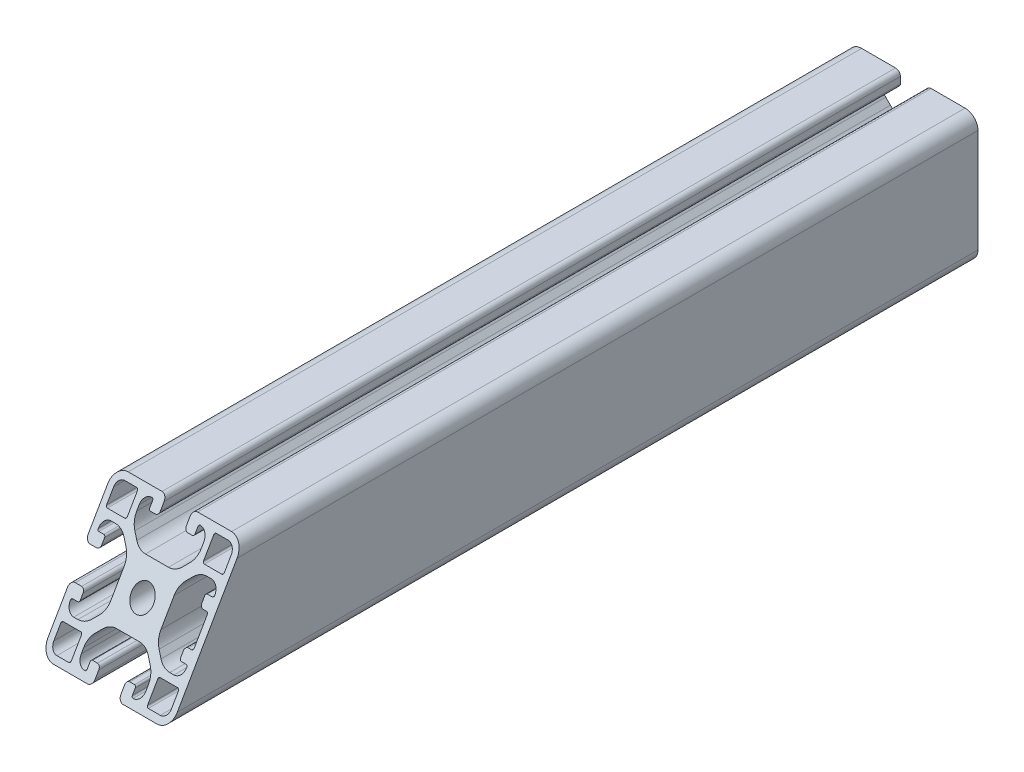
SolidWorks part; units mm, degrees
ref_plane "Piano frontale" through (0, 0, 0) normal (0, 0, 1) x (1, 0, 0)
ref_plane "Piano superiore" through (0, 0, 0) normal (0, 1, 0) x (1, 0, 0)
ref_plane "Piano destro" through (0, 0, 0) normal (1, 0, 0) x (0, 0, -1)
ref_plane "Piano1" through (0, 0, -340) normal (0, 0, -1) x (-1, 0, 0)
sketch "Schizzo1" plane through (0, 0, -340) normal (0, 0, -1) x (-1, 0, 0)
  line L0 (-12.3, -18.2) -> (-16, -18.2)
  line L1 (-18.2, -16) -> (-18.2, -12.3)
  line L2 (-17.7, -11.8) -> (-12.3, -11.8)
  line L3 (-11.8, -12.3) -> (-11.8, -17.7)
  line L4 (-11.8, 17.7) -> (-11.8, 12.3)
  line L5 (-12.3, 11.8) -> (-17.7, 11.8)
  line L6 (-18.2, 12.3) -> (-18.2, 16)
  line L7 (-16, 18.2) -> (-12.3, 18.2)
  line L8 (18.2, 16) -> (18.2, 12.3)
  line L9 (17.7, 11.8) -> (12.3, 11.8)
  line L10 (11.8, 12.3) -> (11.8, 17.7)
  line L11 (12.3, 18.2) -> (16, 18.2)
  line L12 (6.5, -15.5) -> (5, -15.5)
  line L13 (4, -16.5) -> (4, -18.5)
  line L14 (5.5, -20) -> (16, -20)
  line L15 (20, -16) -> (20, -5.5)
  line L16 (18.5, -4) -> (16.5, -4)
  line L17 (15.5, -5) -> (15.5, -6.5)
  line L18 (16, -7) -> (17.55, -7)
  line L19 (18, -7.45) -> (18, -7.5)
  line L20 (15.5, -10) -> (14.1924, -10)
  line L21 (10.6569, -8.5355) -> (9.2145, -7.0931)
  line L22 (7.75, -3.5576) -> (7.75, 3.5576)
  line L23 (9.2145, 7.0931) -> (10.6569, 8.5355)
  line L24 (14.1924, 10) -> (15.5, 10)
  line L25 (18, 7.5) -> (18, 7.45)
  line L26 (17.55, 7) -> (16, 7)
  line L27 (15.5, 6.5) -> (15.5, 5)
  line L28 (16.5, 4) -> (18.5, 4)
  line L29 (20, 5.5) -> (20, 16)
  line L30 (16, 20) -> (5.5, 20)
  line L31 (4, 18.5) -> (4, 16.5)
  line L32 (5, 15.5) -> (6.5, 15.5)
  line L33 (7, 16) -> (7, 17.55)
  line L34 (7.45, 18) -> (7.5, 18)
  line L35 (10, 15.5) -> (10, 14.1924)
  line L36 (8.5355, 10.6569) -> (7.0931, 9.2145)
  line L37 (3.5576, 7.75) -> (-3.5576, 7.75)
  line L38 (-7.0931, 9.2145) -> (-8.5355, 10.6569)
  line L39 (-10, 14.1924) -> (-10, 15.5)
  line L40 (-7.5, 18) -> (-7.45, 18)
  line L41 (-7, 17.55) -> (-7, 16)
  line L42 (-6.5, 15.5) -> (-5, 15.5)
  line L43 (-4, 16.5) -> (-4, 18.5)
  line L44 (-5.5, 20) -> (-16, 20)
  line L45 (-20, 16) -> (-20, -16)
  line L46 (-16, -20) -> (-5.5, -20)
  line L47 (-4, -18.5) -> (-4, -16.5)
  line L48 (-5, -15.5) -> (-6.5, -15.5)
  line L49 (-7, -16) -> (-7, -17.55)
  line L50 (-7.45, -18) -> (-7.5, -18)
  line L51 (-10, -15.5) -> (-10, -14.1924)
  line L52 (-8.5355, -10.6569) -> (-7.0931, -9.2145)
  line L53 (-3.5576, -7.75) -> (3.5576, -7.75)
  line L54 (7.0931, -9.2145) -> (8.5355, -10.6569)
  line L55 (10, -14.1924) -> (10, -15.5)
  line L56 (7.5, -18) -> (7.45, -18)
  line L57 (7, -17.55) -> (7, -16)
  line L58 (18.2, -12.3) -> (18.2, -16)
  line L59 (16, -18.2) -> (12.3, -18.2)
  line L60 (11.8, -17.7) -> (11.8, -12.3)
  line L61 (12.3, -11.8) -> (17.7, -11.8)
  line L62 (-16, 7) -> (-17.5, 7)
  line L63 (-15.5, 10) -> (-14.1924, 10)
  line L64 (-10.6569, 8.5355) -> (-9.2145, 7.0931)
  line L65 (-7.75, 3.5576) -> (-7.75, -3.5576)
  line L66 (-9.2145, -7.0931) -> (-10.6569, -8.5355)
  line L67 (-14.1924, -10) -> (-15.5, -10)
  line L68 (-17.5, -7) -> (-16, -7)
  line L69 (-15.5, -6.5) -> (-15.5, -5)
  line L70 (-16.5, -4) -> (-17.5, -4)
  line L71 (-18, -3.5) -> (-18, 3.5)
  line L72 (-17.5, 4) -> (-16.5, 4)
  line L73 (-15.5, 5) -> (-15.5, 6.5)
  arc A0 (-16, -18.2) -> (-18.2, -16) centre (-16, -16) cw
  arc A1 (-18.2, -12.3) -> (-17.7, -11.8) centre (-17.7, -12.3) cw
  arc A2 (-12.3, -11.8) -> (-11.8, -12.3) centre (-12.3, -12.3) cw
  arc A3 (-11.8, -17.7) -> (-12.3, -18.2) centre (-12.3, -17.7) cw
  arc A4 (-12.3, 18.2) -> (-11.8, 17.7) centre (-12.3, 17.7) cw
  arc A5 (-11.8, 12.3) -> (-12.3, 11.8) centre (-12.3, 12.3) cw
  arc A6 (-17.7, 11.8) -> (-18.2, 12.3) centre (-17.7, 12.3) cw
  arc A7 (-18.2, 16) -> (-16, 18.2) centre (-16, 16) cw
  arc A8 (16, 18.2) -> (18.2, 16) centre (16, 16) cw
  arc A9 (18.2, 12.3) -> (17.7, 11.8) centre (17.7, 12.3) cw
  arc A10 (12.3, 11.8) -> (11.8, 12.3) centre (12.3, 12.3) cw
  arc A11 (11.8, 17.7) -> (12.3, 18.2) centre (12.3, 17.7) cw
  arc A12 (5, -15.5) -> (4, -16.5) centre (5, -16.5) ccw
  arc A13 (4, -18.5) -> (5.5, -20) centre (5.5, -18.5) ccw
  arc A14 (16, -20) -> (20, -16) centre (16, -16) ccw
  arc A15 (20, -5.5) -> (18.5, -4) centre (18.5, -5.5) ccw
  arc A16 (16.5, -4) -> (15.5, -5) centre (16.5, -5) ccw
  arc A17 (15.5, -6.5) -> (16, -7) centre (16, -6.5) ccw
  arc A18 (17.55, -7) -> (18, -7.45) centre (17.55, -7.45) cw
  arc A19 (18, -7.5) -> (15.5, -10) centre (15.5, -7.5) cw
  arc A20 (14.1924, -10) -> (10.6569, -8.5355) centre (14.1924, -5) cw
  arc A21 (9.2145, -7.0931) -> (7.75, -3.5576) centre (12.75, -3.5576) cw
  arc A22 (7.75, 3.5576) -> (9.2145, 7.0931) centre (12.75, 3.5576) cw
  arc A23 (10.6569, 8.5355) -> (14.1924, 10) centre (14.1924, 5) cw
  arc A24 (15.5, 10) -> (18, 7.5) centre (15.5, 7.5) cw
  arc A25 (18, 7.45) -> (17.55, 7) centre (17.55, 7.45) cw
  arc A26 (16, 7) -> (15.5, 6.5) centre (16, 6.5) ccw
  arc A27 (15.5, 5) -> (16.5, 4) centre (16.5, 5) ccw
  arc A28 (18.5, 4) -> (20, 5.5) centre (18.5, 5.5) ccw
  arc A29 (20, 16) -> (16, 20) centre (16, 16) ccw
  arc A30 (5.5, 20) -> (4, 18.5) centre (5.5, 18.5) ccw
  arc A31 (4, 16.5) -> (5, 15.5) centre (5, 16.5) ccw
  arc A32 (6.5, 15.5) -> (7, 16) centre (6.5, 16) ccw
  arc A33 (7, 17.55) -> (7.45, 18) centre (7.45, 17.55) cw
  arc A34 (7.5, 18) -> (10, 15.5) centre (7.5, 15.5) cw
  arc A35 (10, 14.1924) -> (8.5355, 10.6569) centre (5, 14.1924) cw
  arc A36 (7.0931, 9.2145) -> (3.5576, 7.75) centre (3.5576, 12.75) cw
  arc A37 (-3.5576, 7.75) -> (-7.0931, 9.2145) centre (-3.5576, 12.75) cw
  arc A38 (-8.5355, 10.6569) -> (-10, 14.1924) centre (-5, 14.1924) cw
  arc A39 (-10, 15.5) -> (-7.5, 18) centre (-7.5, 15.5) cw
  arc A40 (-7.45, 18) -> (-7, 17.55) centre (-7.45, 17.55) cw
  arc A41 (-7, 16) -> (-6.5, 15.5) centre (-6.5, 16) ccw
  arc A42 (-5, 15.5) -> (-4, 16.5) centre (-5, 16.5) ccw
  arc A43 (-4, 18.5) -> (-5.5, 20) centre (-5.5, 18.5) ccw
  arc A44 (-16, 20) -> (-20, 16) centre (-16, 16) ccw
  arc A45 (-20, -16) -> (-16, -20) centre (-16, -16) ccw
  arc A46 (-5.5, -20) -> (-4, -18.5) centre (-5.5, -18.5) ccw
  arc A47 (-4, -16.5) -> (-5, -15.5) centre (-5, -16.5) ccw
  arc A48 (-6.5, -15.5) -> (-7, -16) centre (-6.5, -16) ccw
  arc A49 (-7, -17.55) -> (-7.45, -18) centre (-7.45, -17.55) cw
  arc A50 (-7.5, -18) -> (-10, -15.5) centre (-7.5, -15.5) cw
  arc A51 (-10, -14.1924) -> (-8.5355, -10.6569) centre (-5, -14.1924) cw
  arc A52 (-7.0931, -9.2145) -> (-3.5576, -7.75) centre (-3.5576, -12.75) cw
  arc A53 (3.5576, -7.75) -> (7.0931, -9.2145) centre (3.5576, -12.75) cw
  arc A54 (8.5355, -10.6569) -> (10, -14.1924) centre (5, -14.1924) cw
  arc A55 (10, -15.5) -> (7.5, -18) centre (7.5, -15.5) cw
  arc A56 (7.45, -18) -> (7, -17.55) centre (7.45, -17.55) cw
  arc A57 (7, -16) -> (6.5, -15.5) centre (6.5, -16) ccw
  arc A58 (17.7, -11.8) -> (18.2, -12.3) centre (17.7, -12.3) cw
  arc A59 (18.2, -16) -> (16, -18.2) centre (16, -16) cw
  arc A60 (12.3, -18.2) -> (11.8, -17.7) centre (12.3, -17.7) cw
  arc A61 (11.8, -12.3) -> (12.3, -11.8) centre (12.3, -12.3) cw
  circle A62 centre (0, 0) radius 3.4
  arc A63 (-15.5, 6.5) -> (-16, 7) centre (-16, 6.5) ccw
  arc A64 (-17.5, 7) -> (-18, 7.5) centre (-17.5, 7.5) cw
  arc A65 (-18, 7.5) -> (-15.5, 10) centre (-15.5, 7.5) cw
  arc A66 (-14.1924, 10) -> (-10.6569, 8.5355) centre (-14.1924, 5) cw
  arc A67 (-9.2145, 7.0931) -> (-7.75, 3.5576) centre (-12.75, 3.5576) cw
  arc A68 (-7.75, -3.5576) -> (-9.2145, -7.0931) centre (-12.75, -3.5576) cw
  arc A69 (-10.6569, -8.5355) -> (-14.1924, -10) centre (-14.1924, -5) cw
  arc A70 (-15.5, -10) -> (-18, -7.5) centre (-15.5, -7.5) cw
  arc A71 (-18, -7.5) -> (-17.5, -7) centre (-17.5, -7.5) cw
  arc A72 (-16, -7) -> (-15.5, -6.5) centre (-16, -6.5) ccw
  arc A73 (-15.5, -5) -> (-16.5, -4) centre (-16.5, -5) ccw
  arc A74 (-17.5, -4) -> (-18, -3.5) centre (-17.5, -3.5) cw
  arc A75 (-18, 3.5) -> (-17.5, 4) centre (-17.5, 3.5) cw
  arc A76 (-16.5, 4) -> (-15.5, 5) centre (-16.5, 5) ccw
extrude "Estrusione-Estrusione1" add sketch "Schizzo1" against normal blind 250
sketch "Schizzo9" plane through (20, 0, 0) normal (1, 0, 0) x (0, 0, -1)
  line L0 (340, -16) -> (340, 16) construction
  line L1 (90, 16) -> (90, -16) construction
  line L2 (340, 16) -> (340, 20) construction
  line L3 (340, 20) -> (90, 20) construction
  line L4 (90, 20) -> (90, 16) construction
  line L5 (340, -20) -> (340, -16) construction
  line L6 (90, -16) -> (90, -20) construction
  line L7 (90, -20) -> (340, -20) construction
  line L8 (340, -16) -> (340, 16)
  line L9 (90, 16) -> (90, -16)
  line L10 (340, 16) -> (340, 20)
  line L11 (340, 20) -> (90, 20)
  line L12 (90, 20) -> (90, 16)
  line L13 (340, -20) -> (340, -16)
  line L14 (90, -16) -> (90, -20)
  line L15 (90, -20) -> (340, -20)
  line L16 (340, 20) -> (316.8895, -20)
  line L17 (90, -20) -> (-536.8844, 20)
  line L18 (90, -20) -> (113.1038, 20)
  line M2 (340, 16) -> (90, 16)
  line M3 (90, 16) -> (90, -16)
  line M4 (90, -16) -> (340, -16)
extrude "Taglio-Estrusione4" cut sketch "Schizzo9" against normal through all contours L14 L18 M4 | L18 M4 M2 M3 | L18 L11 L12 M2 | L15 L13 L8 L10
